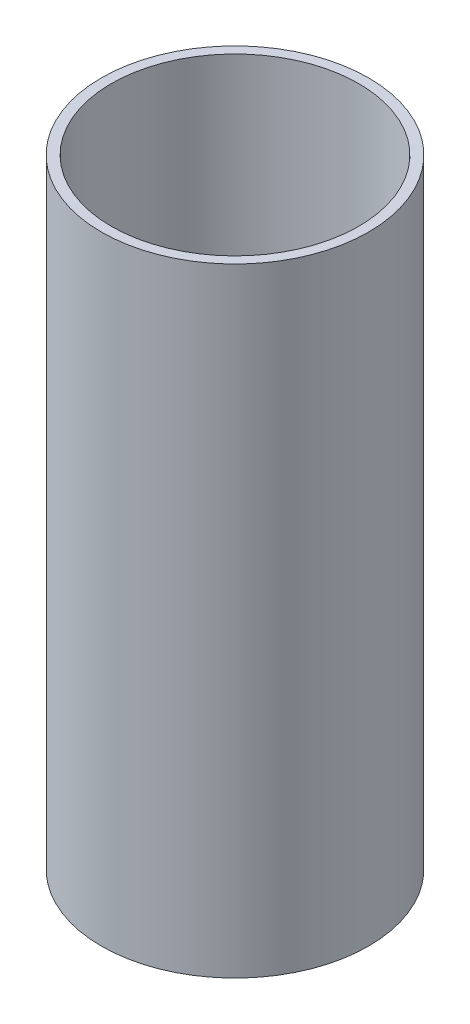
SolidWorks part; units mm, degrees
material "Thornel Mat VMA"
ref_plane "Front Plane" through (0, 0, 0) normal (0, 0, 1) x (1, 0, 0)
ref_plane "Top Plane" through (0, 0, 0) normal (0, 1, 0) x (1, 0, 0)
ref_plane "Right Plane" through (0, 0, 0) normal (1, 0, 0) x (0, 0, -1)
sketch "Sketch2" plane through (0, 0, 0) normal (0, 1, 0) x (1, 0, 0)
  circle A0 centre (0, 0) radius 13.716
  circle A1 centre (0, 0) radius 12.7
  dimension "D1" = 25.4
  dimension "D2" = 1.016
extrude "Boss-Extrude1" add sketch "Sketch2" along normal blind 63.5
